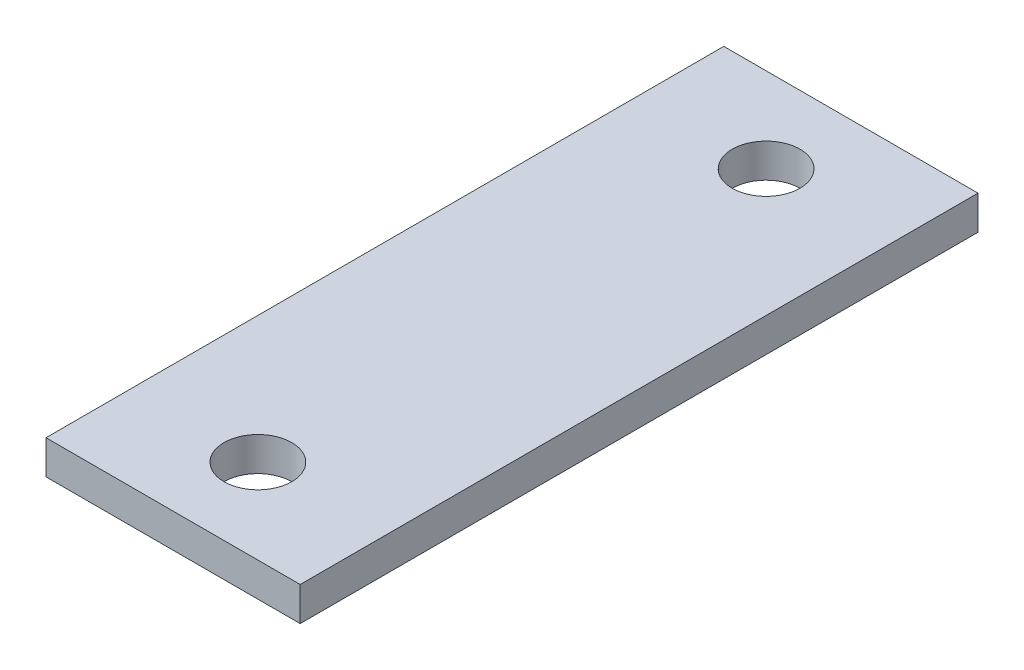
SolidWorks part; units mm, degrees
material "AISI 304"
ref_plane "Front Plane" through (0, 0, 0) normal (0, 0, 1) x (1, 0, 0)
ref_plane "Top Plane" through (0, 0, 0) normal (0, 1, 0) x (1, 0, 0)
ref_plane "Right Plane" through (0, 0, 0) normal (1, 0, 0) x (0, 0, -1)
sketch "Sketch2" plane through (0, 0, 0) normal (0, 1, 0) x (1, 0, 0)
  line L1 (7.5, -20) -> (-7.5, -20)
  line L2 (7.5, -20) -> (7.5, 20)
  line L3 (7.5, 20) -> (-7.5, 20)
  line L4 (-7.5, -20) -> (-7.5, 20)
  line L5 (7.5, -20) -> (-7.5, 20) construction
  line L6 (7.5, 20) -> (-7.5, -20) construction
  point P0 (0, 0)
  dimension "D1" = 15
  dimension "D2" = 40
extrude "Boss-Extrude1" add sketch "Sketch2" along normal blind 2
sketch "Sketch3" plane through (0, 0, 0) normal (0, -1, 0) x (-1, 0, 0)
  circle A0 centre (0, 0) radius 1.5
  dimension "D1" = 3
extrude "Cut-Extrude1" cut sketch "Sketch3" against normal blind 0.5
sketch "Sketch4" plane through (0, 2, 0) normal (0, 1, 0) x (1, 0, 0)
  line L0 (-7.5, 0) -> (7.5, 0) construction
  line L1 (7.5, 20) -> (-7.5, 20) construction
  line L2 (0, 20) -> (0, 10) construction
  line L3 (-7.5, 20) -> (-7.5, -20) construction
  line L5 (7.5, -20) -> (7.5, 20) construction
  circle A0 centre (0, 14.9955) radius 2
  circle A1 centre (0, -14.9955) radius 2
  dimension "D1" = 4
extrude "Cut-Extrude2" cut sketch "Sketch4" against normal blind 10
